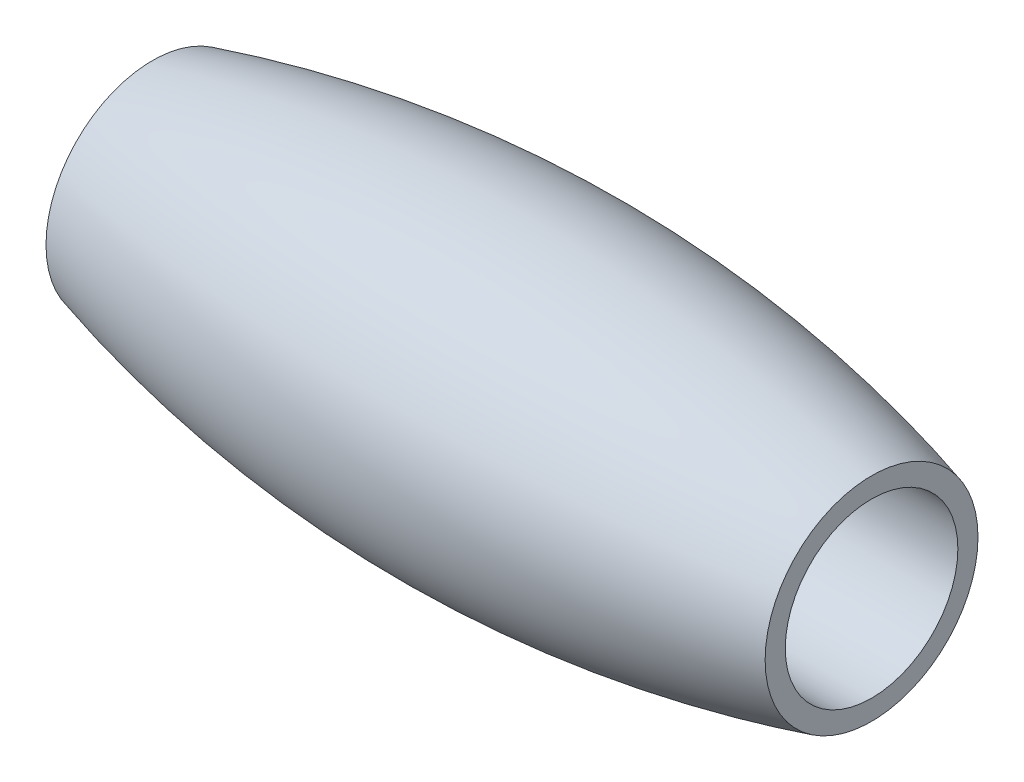
SolidWorks part; units mm, degrees
ref_plane "Front Plane" through (0, 0, 0) normal (0, 0, 1) x (1, 0, 0)
ref_plane "Top Plane" through (0, 0, 0) normal (0, 1, 0) x (1, 0, 0)
ref_plane "Right Plane" through (0, 0, 0) normal (1, 0, 0) x (0, 0, -1)
ref_plane "Plane1" through (0, 0, 0) normal (0, 0, -1) x (-1, 0, 0)
sketch "Sketch1" plane through (0, 0, 0) normal (0, 0, -1) x (-1, 0, 0)
  line L0 (-18.75, 5.55) -> (-18.75, 4.5)
  line L1 (-18.75, 4.5) -> (18.75, 4.5)
  line L2 (18.75, 4.5) -> (18.75, 5.55)
  line L3 (-18.75, 0) -> (18.75, 0) construction
  arc A0 (18.75, 5.55) -> (-18.75, 5.55) centre (0, -62.1088) ccw
  dimension "D1" = 70.2088
  dimension "D2" = 18.75
  dimension "D3" = 4.5
  dimension "D4" = 5.55
revolve "Revolve1" add sketch "Sketch1" angle 360 about L3
